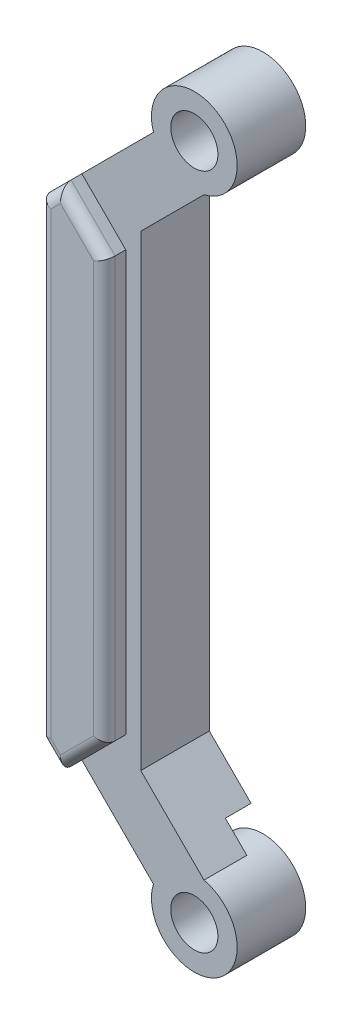
SolidWorks part; units mm, degrees
ref_plane "前视基准面" through (0, 0, 0) normal (0, 0, 1) x (1, 0, 0)
ref_plane "上视基准面" through (0, 0, 0) normal (0, 1, 0) x (1, 0, 0)
ref_plane "右视基准面" through (0, 0, 0) normal (1, 0, 0) x (0, 0, -1)
sketch "草图1" plane through (0, 0, 0) normal (0, 0, 1) x (1, 0, 0)
  line L0 (0, 0) -> (0, 15.8) construction
  line L2 (-6.2, 0) -> (-6.2, 10.9)
  line L3 (-6.2, 10.9) -> (-1.906, 15.194)
  line L5 (-2, 0) -> (-2, 11.4)
  line L6 (-2, 11.4) -> (0.4517, 13.8517)
  line L7 (-6.2, 0) -> (-6.2, -10.9)
  line L8 (-2, 0) -> (-2, -11.4)
  line L9 (0, 0) -> (0, -15.8) construction
  line L10 (-6.2, -10.9) -> (-1.906, -15.194)
  line L11 (-2, -11.4) -> (0.4517, -13.8517)
  circle A0 centre (0, 15.8) radius 1.1 construction
  circle A1 centre (0, 15.8) radius 2 construction
  arc A2 (-1.906, 15.194) -> (0.4517, 13.8517) centre (0, 15.8) cw
  circle A3 centre (0, -15.8) radius 2 construction
  arc A4 (0.4517, -13.8517) -> (-1.906, -15.194) centre (0, -15.8) cw
extrude "凸台-拉伸1" add sketch "草图1" along normal blind 3.2
sketch "草图2" plane through (0, 0, 3.2) normal (0, 0, 1) x (1, 0, 0)
  circle A0 centre (0, 15.8) radius 1.1
  circle A1 centre (0, -15.8) radius 1.1
extrude "切除-拉伸1" cut sketch "草图2" against normal blind 3.2
sketch "草图3" plane through (0, 0, 3.2) normal (0, 0, 1) x (1, 0, 0)
  line L0 (0, 0) -> (-3.2, 0) construction
  line L1 (-3.2, 0) -> (-3.2, 9.8)
  line L2 (-3.2, 9.8) -> (-5.25, 11.85)
  line L3 (-1.906, 15.194) -> (-6.2, 10.9) construction
  line L4 (-5.25, 11.85) -> (-6.2, 10.9)
  line L5 (-6.2, 10.9) -> (-6.2, -10.9) construction
  line L6 (-6.2, 10.9) -> (-6.2, -10.9)
  line L7 (-3.2, 0) -> (-3.2, -9.8)
  line L8 (-3.2, -9.8) -> (-5.25, -11.85)
  line L9 (-6.2, -10.9) -> (-1.906, -15.194) construction
  line L10 (-5.25, -11.85) -> (-6.2, -10.9)
extrude "凸台-拉伸2" add sketch "草图3" along normal blind 1 contours L10 L6 L4 L2 L1 L7 L8
fillet "圆角2" radius 0.5 6 edges at (-5.725, -11.375, 4.2) (-6.2, 0, 4.2) (-5.725, 11.375, 4.2) (-4.225, 10.825, 4.2) (-3.2, 0, 4.2) (-4.225, -10.825, 4.2)
sketch "草图7" plane through (0, 0, 0) normal (0, 0, 1) x (1, 0, 0)
  line L0 (-5.25, 11.1429) -> (-3.7, 9.5929)
  line L1 (-3.7, 9.5929) -> (-3.7, -9.5929)
  line L2 (-3.7, -9.5929) -> (-5.25, -11.1429)
  line L3 (-5.25, -11.1429) -> (-5.7, -10.6929)
  line L4 (-5.7, -10.6929) -> (-5.7, 10.6929)
  line L5 (-5.7, 10.6929) -> (-5.25, 11.1429)
extrude "切除-拉伸10" cut sketch "草图7" along normal blind 3.7
sketch "草图9" plane through (0, 0, 0) normal (0, 0, -1) x (-1, 0, 0)
  line L0 (3.7, 9.5929) -> (3.2, 9.5929)
  line L1 (3.7, -9.5929) -> (3.7, 9.5929) construction
  line L2 (3.2, 0) -> (3.2, 11) construction
  line L3 (3.7, 9.5929) -> (3.7, -9.5929)
  line L4 (3.7, -9.5929) -> (3.2, -9.5929)
  line L5 (3.2, -9.5929) -> (3.2, 9.5929)
extrude "切除-拉伸11" cut sketch "草图9" against normal blind 2
sketch "草图10" plane through (0, 0, 3.2) normal (0, 0, 1) x (1, 0, 0)
  line L0 (-2.5, 10.9) -> (-2.5, -10.9)
  line L2 (-2.5, -10.9) -> (-2, -11.4)
  line L3 (-2, -11.4) -> (-2, 11.4)
  line L4 (-2.5, 10.9) -> (-2, 11.4)
extrude "切除-拉伸12" cut sketch "草图10" against normal blind 3.2
sketch "草图12" plane through (0, 0, 0) normal (0, 0, -1) x (-1, 0, 0)
  line L0 (3.6314, 10.6172) -> (4.6328, 11.6186)
  line L1 (1.8044, -14.4471) -> (0.8029, -13.4456)
  line L2 (4.6328, 11.6186) -> (1.8044, 14.4471)
  line L3 (1.8044, 14.4471) -> (0.8029, 13.4456)
  line L5 (0.8029, 13.4456) -> (3.6314, 10.6172)
  line L6 (0.8029, -13.4456) -> (3.6314, -10.6172)
  line L7 (3.6314, -10.6172) -> (4.6328, -11.6186)
  line L9 (4.6328, -11.6186) -> (1.8044, -14.4471)
extrude "切除-拉伸13" cut sketch "草图12" against normal blind 2.2
sketch "草图14" plane through (0, 0, 0) normal (0, 0, -1) x (-1, 0, 0)
  line L0 (2.5, 10.9) -> (-0.4517, 13.8517) construction
  line L1 (1.906, 15.194) -> (6.2, 10.9) construction
  line L2 (6.2, -10.9) -> (1.906, -15.194) construction
  line L3 (-0.4517, -13.8517) -> (2.5, -10.9) construction
  line L4 (1.906, -15.194) -> (2.6693, -14.4307)
  line L5 (-0.4517, -13.8517) -> (0.5493, -12.8507)
  line L6 (-0.4517, 13.8517) -> (0.5493, 12.8507)
  line L8 (2.6693, 14.4307) -> (1.906, 15.194)
  arc A0 (-0.4517, 13.8517) -> (1.906, 15.194) centre (0, 15.8) ccw
  arc A1 (1.906, 15.194) -> (-0.4517, 13.8517) centre (0, 15.8) ccw construction
  arc A2 (0.5493, 12.8507) -> (2.6693, 14.4307) centre (0, 15.8) ccw
  arc A3 (-0.4517, -13.8517) -> (1.906, -15.194) centre (0, -15.8) cw
  arc A4 (-0.4517, -13.8517) -> (1.906, -15.194) centre (0, -15.8) ccw construction
  arc A5 (2.6693, -14.4307) -> (0.5493, -12.8507) centre (0, -15.8) ccw
extrude "切除-拉伸14" cut sketch "草图14" against normal blind 1.2
sketch "草图15" plane through (0, 0, 0) normal (0, 0, -1) x (-1, 0, 0)
  line L0 (3.2, 0) -> (3.2, 1.5) construction
  line L1 (3.2, 9.5929) -> (3.2, -9.5929) construction
  line L2 (3.2, 9.5929) -> (3.2, -9.5929) construction
  line L3 (5.7, 10.6929) -> (5.7, -10.6929) construction
  line L4 (3.2, 1.5) -> (5.7, 1.5)
  line L5 (3.2, 1.5) -> (3.2, 2.5)
  line L6 (3.2, 2.5) -> (5.7, 2.5)
  line L7 (5.7, 1.5) -> (5.7, 2.5)
  line L8 (3.2, 0) -> (3.2, -1.5) construction
  line L10 (3.2, -1.5) -> (5.7, -1.5)
  line L11 (3.2, -1.5) -> (3.2, -2.5)
  line L12 (3.2, -2.5) -> (5.7, -2.5)
  line L13 (5.7, -1.5) -> (5.7, -2.5)
  point P15 (0, 0)
extrude "凸台-拉伸3" add sketch "草图15" against normal blind 1
